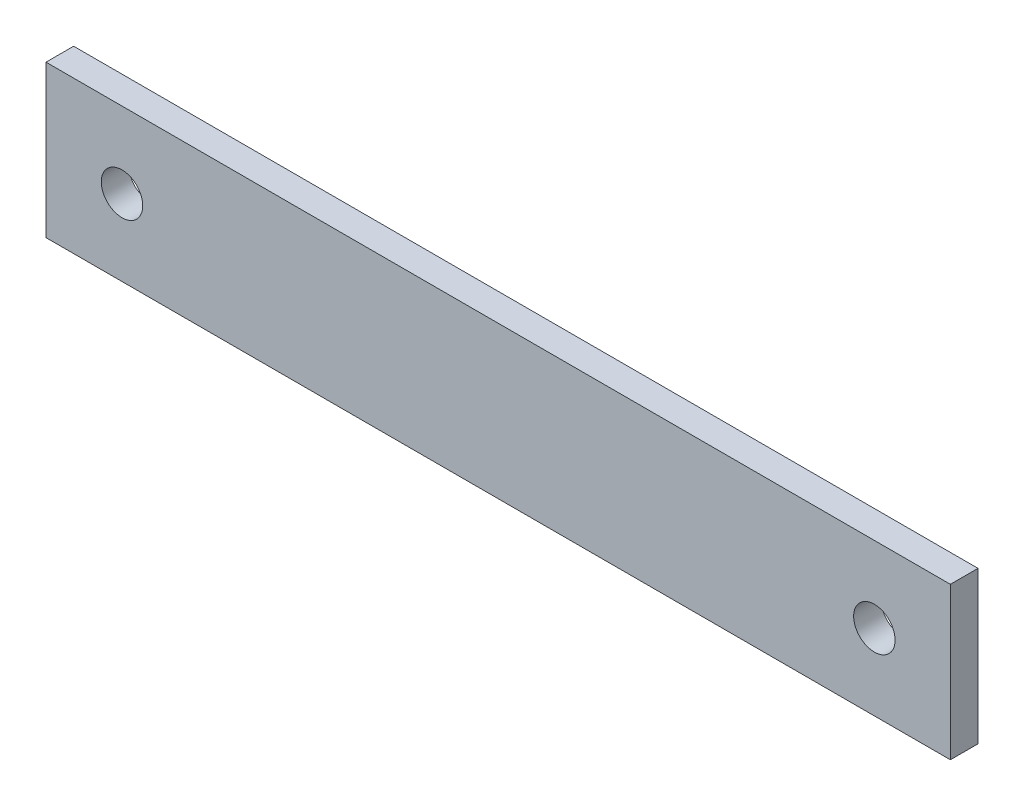
SolidWorks part; units mm, degrees
ref_plane "前视基准面" through (0, 0, 0) normal (0, 0, 1) x (1, 0, 0)
ref_plane "上视基准面" through (0, 0, 0) normal (0, 1, 0) x (1, 0, 0)
ref_plane "右视基准面" through (0, 0, 0) normal (1, 0, 0) x (0, 0, -1)
other "Configuration Table"
sketch "草图1" plane through (0, 0, 0) normal (0, 0, 1) x (1, 0, 0)
  line L1 (-11, -11) -> (119.9, -11)
  line L2 (-11, -11) -> (-11, 11)
  line L3 (-11, 11) -> (119.9, 11)
  line L4 (119.9, -11) -> (119.9, 11)
  line L5 (-11, -11) -> (119.9, 11) construction
  line L6 (-11, 11) -> (119.9, -11) construction
  circle A0 centre (0, 0) radius 3
  circle A1 centre (108.9, 0) radius 3
  point P0 (54.45, 0)
extrude "凸台-拉伸1" add sketch "草图1" along normal mid plane 4
